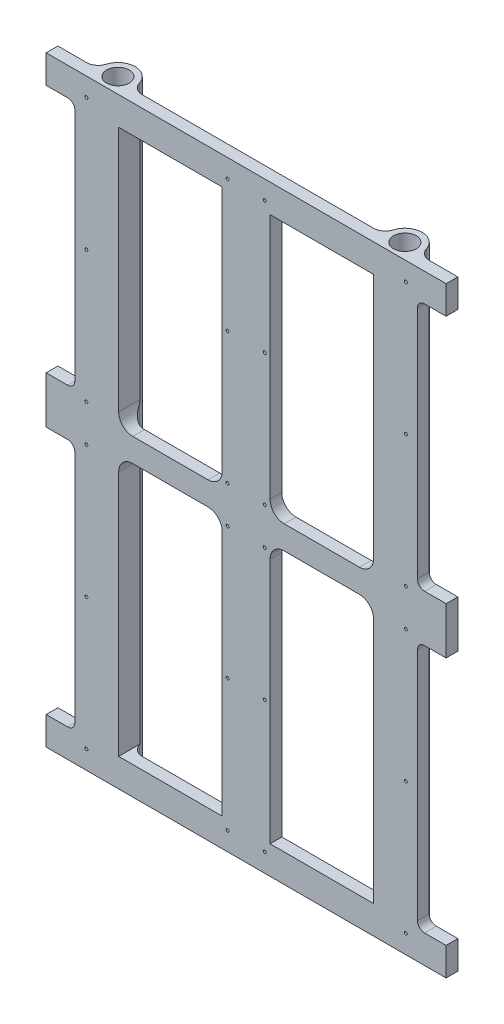
SolidWorks part; units mm, degrees
material "E-Glass Fiber"
ref_plane "Front Plane" through (0, 0, 0) normal (0, 0, 1) x (1, 0, 0)
ref_plane "Top Plane" through (0, 0, 0) normal (0, 1, 0) x (1, 0, 0)
ref_plane "Right Plane" through (0, 0, 0) normal (1, 0, 0) x (0, 0, -1)
other "Center of Mass"
sketch "Sketch1" plane through (0, 0, 0) normal (0, 1, 0) x (1, 0, 0)
  line L19 (85, -5) -> (85, 0)
  line L20 (85, -5) -> (-85, -5)
  line L24 (85, 0) -> (72.8176, 0)
  line L25 (-85, -5) -> (-85, 0)
  line L26 (85, -5) -> (-85, 0) construction
  line L27 (85, 0) -> (-85, -5) construction
  line L28 (0, 0) -> (0, -5) construction
  line L29 (-72.8176, 0) -> (-85, 0)
  line L30 (49.1824, 0) -> (-49.1824, 0)
  circle A29 centre (-61, 1.5) radius 4.825
  arc A30 (-68.1698, 0) -> (-53.8302, 0) centre (-61, 1.5) ccw construction
  arc A31 (-72.8176, 0) -> (-68.0234, 3.5801) centre (-72.8176, 5) ccw
  arc A32 (-53.9766, 3.5801) -> (-49.1824, 0) centre (-49.1824, 5) ccw
  arc A33 (-53.9766, 3.5801) -> (-68.0234, 3.5801) centre (-61, 1.5) ccw
  arc A34 (68.1698, 0) -> (53.8302, 0) centre (61, 1.5) cw construction
  arc A35 (53.9766, 3.5801) -> (68.0234, 3.5801) centre (61, 1.5) cw
  arc A36 (53.9766, 3.5801) -> (49.1824, 0) centre (49.1824, 5) cw
  arc A37 (72.8176, 0) -> (68.0234, 3.5801) centre (72.8176, 5) cw
  circle A38 centre (61, 1.5) radius 4.825
  point P1 (0, -2.5)
  dimension "D3" = 9.65
  dimension "D4" = 6.5
  dimension "D5" = 61
  dimension "D6" = 14.65
  dimension "D1" = 5
  dimension "D2" = 170
extrude "Boss-Extrude1" add sketch "Sketch1" along normal blind 255.6
sketch "Sketch2" plane through (0, 0, 0) normal (0, 0, -1) x (-1, 0, 0)
  line L0 (0, 127.8) -> (-255.8, 127.8) construction
  line L5 (-56.175, 0) -> (-56.175, 550) construction
  line L6 (-54.175, 243.6) -> (-10.175, 243.6)
  line L7 (0, 255.6) -> (-255.8, 255.6) construction
  line L9 (-65.825, 550) -> (-65.825, 0) construction
  line L15 (-54.175, 243.6) -> (-54.175, 138.8)
  line L16 (-48.175, 132.8) -> (-16.175, 132.8)
  line L17 (-87.825, 137.8) -> (-75.825, 137.8)
  line L18 (-10.175, 243.6) -> (-10.175, 138.8)
  line L31 (-54.175, 243.6) -> (-10.175, 132.8) construction
  line L32 (-54.175, 132.8) -> (-10.175, 243.6) construction
  line L33 (-87.825, 12) -> (-72.825, 117.8) construction
  line L35 (-87.825, 137.8) -> (-87.825, 243.6)
  line L36 (-87.825, 243.6) -> (-75.825, 243.6)
  line L37 (-72.825, 140.8) -> (-72.825, 240.6)
  line L38 (-87.825, 137.8) -> (-72.825, 243.6) construction
  line L39 (-87.825, 243.6) -> (-72.825, 137.8) construction
  line L40 (-87.825, 117.8) -> (-72.825, 12) construction
  line L41 (-54.175, 122.8) -> (-10.175, 12) construction
  line L42 (-54.175, 12) -> (-10.175, 122.8) construction
  line L43 (-72.825, 114.8) -> (-72.825, 15)
  line L44 (-87.825, 12) -> (-75.825, 12)
  line L45 (-87.825, 117.8) -> (-87.825, 12)
  line L46 (-10.175, 12) -> (-10.175, 116.8)
  line L47 (-87.825, 117.8) -> (-75.825, 117.8)
  line L48 (-48.175, 122.8) -> (-16.175, 122.8)
  line L49 (-54.175, 12) -> (-54.175, 116.8)
  line L50 (-54.175, 12) -> (-10.175, 12)
  line L51 (0, 255.6) -> (0, 127.8) construction
  line L52 (54.175, 12) -> (10.175, 122.8) construction
  line L53 (54.175, 122.8) -> (10.175, 12) construction
  line L54 (87.825, 117.8) -> (72.825, 12) construction
  line L55 (87.825, 243.6) -> (72.825, 137.8) construction
  line L56 (87.825, 137.8) -> (72.825, 243.6) construction
  line L57 (87.825, 12) -> (72.825, 117.8) construction
  line L58 (54.175, 132.8) -> (10.175, 243.6) construction
  line L59 (54.175, 243.6) -> (10.175, 132.8) construction
  line L60 (54.175, 12) -> (10.175, 12)
  line L61 (54.175, 12) -> (54.175, 116.8)
  line L62 (48.175, 122.8) -> (16.175, 122.8)
  line L63 (87.825, 117.8) -> (75.825, 117.8)
  line L64 (10.175, 12) -> (10.175, 116.8)
  line L65 (87.825, 117.8) -> (87.825, 12)
  line L66 (87.825, 12) -> (75.825, 12)
  line L67 (72.825, 114.8) -> (72.825, 15)
  line L68 (72.825, 140.8) -> (72.825, 240.6)
  line L69 (87.825, 243.6) -> (75.825, 243.6)
  line L70 (87.825, 137.8) -> (87.825, 243.6)
  line L71 (10.175, 243.6) -> (10.175, 138.8)
  line L72 (87.825, 137.8) -> (75.825, 137.8)
  line L73 (48.175, 132.8) -> (16.175, 132.8)
  line L74 (54.175, 243.6) -> (54.175, 138.8)
  line L75 (54.175, 243.6) -> (10.175, 243.6)
  arc A0 (-10.175, 138.8) -> (-16.175, 132.8) centre (-16.175, 138.8) cw
  arc A1 (-54.175, 138.8) -> (-48.175, 132.8) centre (-48.175, 138.8) ccw
  arc A2 (-75.825, 137.8) -> (-72.825, 140.8) centre (-75.825, 140.8) ccw
  arc A3 (-72.825, 240.6) -> (-75.825, 243.6) centre (-75.825, 240.6) ccw
  arc A4 (-72.825, 15) -> (-75.825, 12) centre (-75.825, 15) cw
  arc A5 (-75.825, 117.8) -> (-72.825, 114.8) centre (-75.825, 114.8) cw
  arc A6 (-54.175, 116.8) -> (-48.175, 122.8) centre (-48.175, 116.8) cw
  arc A7 (-10.175, 116.8) -> (-16.175, 122.8) centre (-16.175, 116.8) ccw
  arc A8 (10.175, 116.8) -> (16.175, 122.8) centre (16.175, 116.8) cw
  arc A9 (54.175, 116.8) -> (48.175, 122.8) centre (48.175, 116.8) ccw
  arc A10 (75.825, 117.8) -> (72.825, 114.8) centre (75.825, 114.8) ccw
  arc A11 (72.825, 15) -> (75.825, 12) centre (75.825, 15) ccw
  arc A12 (72.825, 240.6) -> (75.825, 243.6) centre (75.825, 240.6) cw
  arc A13 (75.825, 137.8) -> (72.825, 140.8) centre (75.825, 140.8) cw
  arc A14 (54.175, 138.8) -> (48.175, 132.8) centre (48.175, 138.8) cw
  arc A15 (10.175, 138.8) -> (16.175, 132.8) centre (16.175, 138.8) ccw
  point P0 (-32.175, 188.2)
  point P11 (-80.325, 190.7)
  point P44 (-80.325, 64.9)
  point P45 (-32.175, 67.4)
  point P94 (32.175, 67.4)
  point P95 (80.325, 64.9)
  point P96 (80.325, 190.7)
  point P97 (32.175, 188.2)
  dimension "D8" = 6
  dimension "D9" = 3
  dimension "D1" = 44
  dimension "D2" = 2
  dimension "D3" = 12
  dimension "D4" = 5
  dimension "D5" = 7
  dimension "D6" = 15
  dimension "D7" = 10
extrude "Cut-Extrude2" cut sketch "Sketch2" against normal through all and the other way through all
sketch "Sketch3" plane through (0, 0, 5) normal (0, 0, -1) x (-1, 0, 0)
  line L0 (0, 0) -> (0, 255.6) construction
  line L1 (-49.1824, 0) -> (49.1824, 0) construction
  line L5 (0, 255.6) -> (255.8, 255.6) construction
  line L6 (0, 127.8) -> (-255.8, 127.8) construction
  point P0 (-67.9, 7.9)
  point P1 (-7.9, 7.9)
  point P3 (-7.9, 63.9)
  point P5 (-67.9, 63.9)
  point P7 (-67.9, 119.9)
  point P9 (-7.9, 119.9)
  point P23 (7.9, 119.9)
  point P24 (67.9, 119.9)
  point P25 (67.9, 63.9)
  point P26 (7.9, 63.9)
  point P27 (7.9, 7.9)
  point P28 (67.9, 7.9)
  point P31 (67.9, 503.3)
  point P32 (7.9, 503.3)
  point P33 (7.9, 447.3)
  point P34 (67.9, 447.3)
  point P35 (67.9, 391.3)
  point P36 (7.9, 391.3)
  point P37 (-7.9, 391.3)
  point P38 (-67.9, 391.3)
  point P39 (-67.9, 447.3)
  point P40 (-7.9, 447.3)
  point P41 (-7.9, 503.3)
  point P42 (-67.9, 503.3)
  point P46 (67.9, 247.7)
  point P47 (7.9, 247.7)
  point P48 (7.9, 191.7)
  point P49 (67.9, 191.7)
  point P50 (67.9, 135.7)
  point P51 (7.9, 135.7)
  point P52 (-7.9, 135.7)
  point P53 (-67.9, 135.7)
  point P54 (-67.9, 191.7)
  point P55 (-7.9, 191.7)
  point P56 (-7.9, 247.7)
  point P57 (-67.9, 247.7)
hole_wizard "Ø1.25 (1.25) Diameter Hole1" positions "Sketch3" profile "Sketch4" hole size "Ø1.25" standard "ANSI Metric" end condition through all
sketch "Sketch4" plane through (67.9, 7.9, 5) normal (1, 0, 0) x (0, -1, 0)
  line L0 (0, 0) -> (0, 13.825)
  line L1 (0, 13.825) -> (0.625, 13.825)
  line L2 (0.625, 13.825) -> (0.625, 0)
  line L5 (0.625, 0) -> (0, 0)
  line L11 (0, -6.35) -> (0, 107.95) construction
  dimension "Thru Hole Dia." = 1.25
  dimension "Thru Hole Depth" = 13.825
sketch "Sketch5" plane through (0, 0, 0) normal (0, 0, -1) x (-1, 0, 0)
  line L2 (0, 255.6) -> (0, 127.8) construction
  line L3 (0, 127.8) -> (-255.8, 127.8) construction
  circle A24 centre (-67.9, 247.7) radius 1.5
  circle A25 centre (-7.9, 247.7) radius 1.5
  circle A26 centre (-67.9, 191.7) radius 1.5
  circle A27 centre (-67.9, 135.7) radius 1.5
  circle A28 centre (-7.9, 135.7) radius 1.5
  circle A29 centre (-7.9, 191.7) radius 1.5
  circle A48 centre (7.9, 191.7) radius 1.5
  circle A49 centre (7.9, 135.7) radius 1.5
  circle A50 centre (67.9, 135.7) radius 1.5
  circle A51 centre (67.9, 191.7) radius 1.5
  circle A52 centre (7.9, 247.7) radius 1.5
  circle A53 centre (67.9, 247.7) radius 1.5
  circle A54 centre (67.9, 7.9) radius 1.5
  circle A55 centre (7.9, 7.9) radius 1.5
  circle A56 centre (67.9, 63.9) radius 1.5
  circle A57 centre (67.9, 119.9) radius 1.5
  circle A58 centre (7.9, 119.9) radius 1.5
  circle A59 centre (7.9, 63.9) radius 1.5
  circle A60 centre (-7.9, 63.9) radius 1.5
  circle A61 centre (-7.9, 119.9) radius 1.5
  circle A62 centre (-67.9, 119.9) radius 1.5
  circle A63 centre (-67.9, 63.9) radius 1.5
  circle A64 centre (-7.9, 7.9) radius 1.5
  circle A65 centre (-67.9, 7.9) radius 1.5
  dimension "D1" = 3
extrude "Cut-Extrude3" cut sketch "Sketch5" along normal through all
equation "\"rod_d\"= 9.65"
equation "\"big_bearing_id\"= 140mm"
equation "\"rod_offset_c2c\"= \"big_bearing_id\" / 2 - \"rod_d\" / 2 - 1.5"
